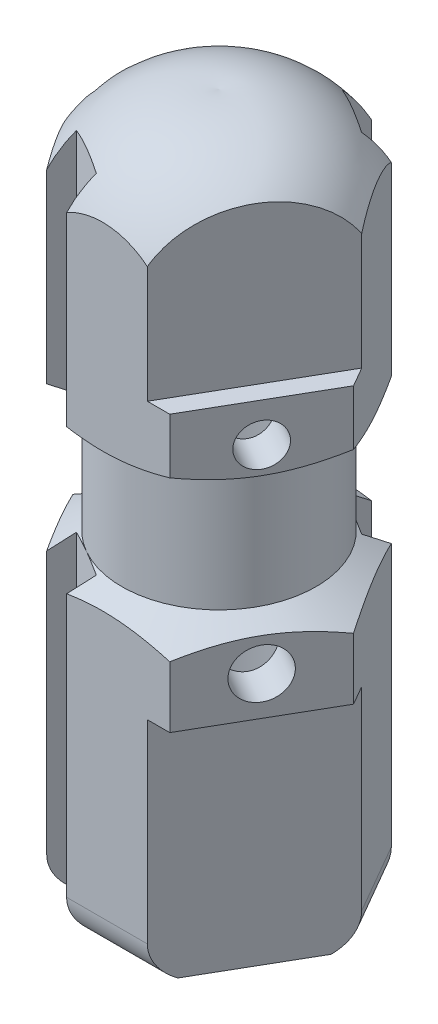
SolidWorks part; units mm, degrees
ref_plane "Front Plane" through (0, 0, 0) normal (0, 0, 1) x (1, 0, 0)
ref_plane "Top Plane" through (0, 0, 0) normal (0, 1, 0) x (1, 0, 0)
ref_plane "Right Plane" through (0, 0, 0) normal (1, 0, 0) x (0, 0, -1)
sketch "Sketch1" plane through (0, 0, 0) normal (0, 1, 0) x (1, 0, 0)
  line L1 (10.9985, 0) -> (5.4993, 9.525)
  line L2 (5.4993, 9.525) -> (-5.4993, 9.525)
  line L3 (-5.4993, 9.525) -> (-10.9985, 0)
  line L4 (-10.9985, 0) -> (-5.4993, -9.525)
  line L5 (-5.4993, -9.525) -> (5.4993, -9.525)
  line L6 (5.4993, -9.525) -> (10.9985, 0)
  circle A0 centre (0, 0) radius 9.525 construction
  dimension "D1" = 19.05
extrude "Boss-Extrude1" add sketch "Sketch1" along normal blind 57.15
fillet "Fillet1" radius 3.175 6 edges at (8.2489, 0, -4.7625) (0, 0, -9.525) (-8.2489, 0, -4.7625) (-8.2489, 0, 4.7625) (0, 0, 9.525) (8.2489, 0, 4.7625)
hole_wizard "1/2 (0.5) Diameter Hole1" positions "Sketch4" profile "Sketch5" hole size "1/2" standard "ANSI Inch"
sketch "Sketch4" plane through (0, 0, 0) normal (0, -1, 0) x (-1, 0, 0)
  point P0 (0, 0)
sketch "Sketch5" plane through (0, 0, 0) normal (1, 0, 0) x (0, 0, -1)
  line L0 (0, 0) -> (0, 49.5355)
  line L1 (0, 49.5355) -> (6.35, 45.72)
  line L2 (6.35, 45.72) -> (6.35, 0)
  line L5 (6.35, 0) -> (0, 0)
  line L10 (0, 49.5355) -> (-6.35, 45.72) construction
  line L11 (0, -6.35) -> (0, 107.95) construction
  dimension "Hole Dia." = 12.7
  dimension "Hole Depth" = 45.72
  dimension "Drill Angle" = 118
hole_wizard "#10-32 Tapped Hole1" positions "Sketch7" profile "Sketch8" tap size "#10-32" standard "ANSI Inch"
sketch "Sketch7" plane through (8.2489, 0, 4.7625) normal (0.866, 0, 0.5) x (0.5, 0, -0.866)
  line L0 (-5.4993, 0) -> (5.4993, 0) construction
  point P0 (0, 22.225)
  point P5 (0, 0)
  dimension "D1" = 22.225
sketch "Sketch8" plane through (8.2489, 22.225, 4.7625) normal (0, 1, 0) x (0.5, 0, -0.866)
  line L0 (0, 0) -> (0, 3.175)
  line L1 (0, 3.175) -> (2.0193, 3.175)
  line L2 (2.0193, 3.175) -> (2.0193, 0)
  line L5 (2.0193, 0) -> (0, 0)
  line L11 (0, -6.35) -> (0, 107.95) construction
  dimension "Thru Tap Drill Dia." = 4.0386
  dimension "Thru Tap Drill Depth" = 3.175
cosmetic thread "Hole Thread1" parameters "D2"=4.826
hole_wizard "#29 (0.136) Diameter Hole1" positions "Sketch10" profile "Sketch11" hole size "#29" standard "ANSI Inch"
sketch "Sketch10" plane through (8.2489, 0, 4.7625) normal (0.866, 0, 0.5) x (0.5, 0, -0.866)
  line L0 (-5.4993, 0) -> (5.4993, 0) construction
  point P0 (0, 38.4175)
  dimension "D1" = 38.4175
sketch "Sketch11" plane through (8.2489, 38.4175, 4.7625) normal (0, 1, 0) x (0.5, 0, -0.866)
  line L0 (0, 0) -> (0, 3.175)
  line L1 (0, 3.175) -> (1.7272, 3.175)
  line L2 (1.7272, 3.175) -> (1.7272, 0)
  line L5 (1.7272, 0) -> (0, 0)
  line L11 (0, -6.35) -> (0, 107.95) construction
  dimension "Thru Hole Dia." = 3.4544
  dimension "Thru Hole Depth" = 3.175
sketch "Sketch12" plane through (0, 0, 0) normal (0, 0, 1) x (1, 0, 0)
  line L0 (0, 0) -> (0, 58.7819) construction
  line L5 (7.9375, 35.3167) -> (10.9985, 37.084)
  line L6 (10.9985, 37.084) -> (10.9985, 24.0665)
  line L7 (10.9985, 24.0665) -> (7.9375, 25.8338)
  line L8 (7.9375, 35.3167) -> (7.9375, 25.8338)
  line L9 (10.9985, 57.15) -> (10.9985, 3.175) construction
  ellipse E2 centre (8.2489, 22.225) end of major axis (8.2489, 20.2057) minor radius 1.0096 construction
  dimension "D2" = 1.8415
  dimension "D4" = 60
  dimension "D5" = 60
sketch "Sketch13" plane through (0, 57.15, 0) normal (0, 1, 0) x (1, 0, 0)
  line L0 (-9.0685, 11.2621) -> (-5.8935, 5.7628)
  line L1 (-9.0685, 11.2621) -> (-5.219, 13.4846)
  line L2 (-5.8935, 5.7628) -> (-2.044, 7.9853)
  line L3 (-5.219, 13.4846) -> (-2.044, 7.9853)
  line L4 (5.4993, 9.525) -> (-5.4993, 9.525) construction
  circle A0 centre (0, 0) radius 9.525 construction
  circle A1 centre (0, 0) radius 7.9375 construction
  dimension "D5" = 1.5875
  dimension "D1" = 120
  dimension "D2" = 6.35
  dimension "D3" = 4.445
  dimension "D4" = 2.2225
extrude "Cut-Extrude1" cut sketch "Sketch13" against normal through all
pattern_circular "CirPattern1" count 6 over 360 about axis through (0, 0, 0) along (0, 1, 0) skipping 2, 3 of "Cut-Extrude1"
sketch "Sketch15" plane through (0, 0, 0) normal (0, 0, 1) x (1, 0, 0)
  line L1 (-10.9985, 47.244) -> (-10.9985, 57.781) construction
  line L4 (-10.9985, 47.244) -> (-21.7515, 47.244)
  line L5 (-21.7515, 47.244) -> (-21.7515, 61.4689)
  line L6 (-21.7515, 61.4689) -> (0, 61.4689)
  line L7 (0, 61.4689) -> (0, 57.0896)
  line L9 (-10.9985, 57.15) -> (-10.9985, 0) construction
  arc A0 (0, 57.0896) -> (-10.9985, 47.244) centre (-1.0925, 47.244) ccw
revolve "Cut-Revolve4" cut sketch "Sketch15" angle 360 about L7
revolve "Cut-Revolve6" cut sketch "Sketch12" angle 360 about L0
sketch "Sketch16" plane through (8.2489, 0, 4.7625) normal (0.866, 0, 0.5) x (0.5, 0, -0.866)
  line L1 (-12.7, 66.9925) -> (12.7, 66.9925)
  line L2 (-12.7, 66.9925) -> (-12.7, 41.5925)
  line L3 (-12.7, 41.5925) -> (12.7, 41.5925)
  line L4 (12.7, 66.9925) -> (12.7, 41.5925)
  line L5 (-12.7, 19.05) -> (12.7, 19.05)
  line L6 (-12.7, 19.05) -> (-12.7, -6.35)
  line L7 (-12.7, -6.35) -> (12.7, -6.35)
  line L8 (12.7, 19.05) -> (12.7, -6.35)
  circle A0 centre (0, 38.4175) radius 1.7272 construction
  circle A1 centre (0, 22.225) radius 2.0193 construction
  dimension "D1" = 3.175
  dimension "D2" = 25.4
  dimension "D3" = 12.7
  dimension "D4" = 25.4
  dimension "D5" = 3.175
  dimension "D6" = 25.4
extrude "Cut-Extrude2" cut sketch "Sketch16" against normal blind 1.5875
